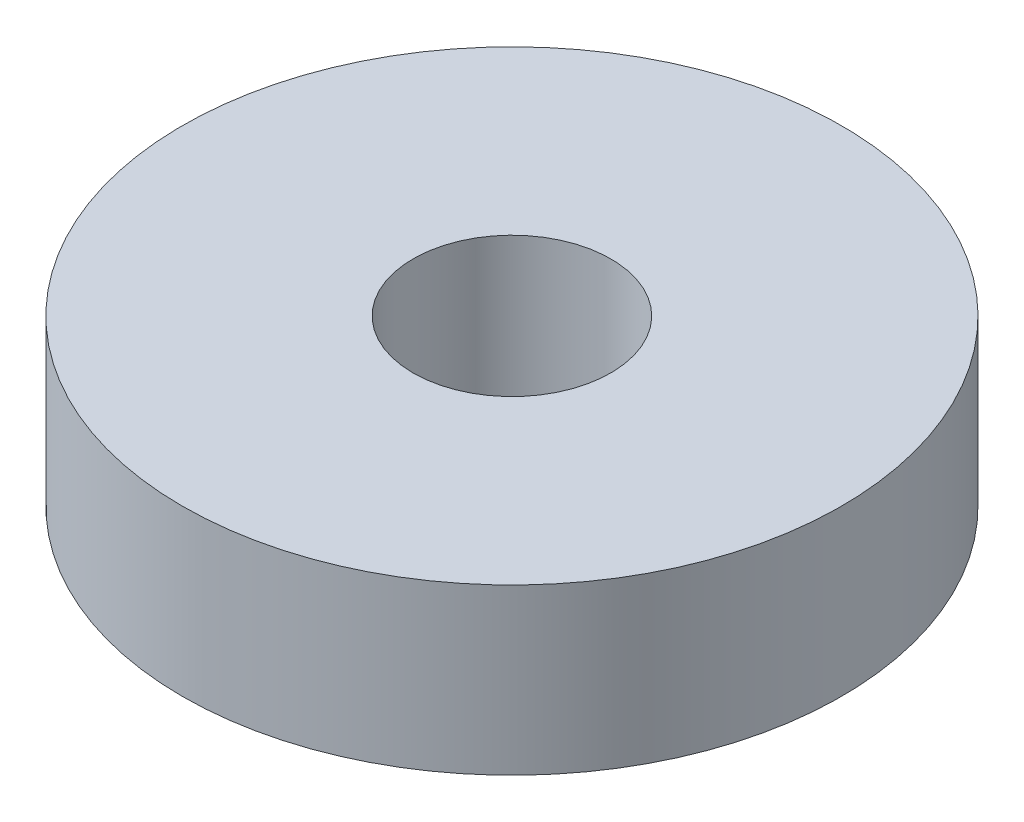
SolidWorks part; units mm, degrees
ref_plane "前视基准面" through (0, 0, 0) normal (0, 0, 1) x (1, 0, 0)
ref_plane "上视基准面" through (0, 0, 0) normal (0, 1, 0) x (1, 0, 0)
ref_plane "右视基准面" through (0, 0, 0) normal (1, 0, 0) x (0, 0, -1)
sketch "草图1" plane through (0, 0, 0) normal (0, 1, 0) x (1, 0, 0)
  circle A0 centre (0, 0) radius 10
  dimension "D1" = 20
extrude "凸台-拉伸1" add sketch "草图1" along normal blind 5
sketch "草图2" plane through (0, 5, 0) normal (0, 1, 0) x (1, 0, 0)
  circle A0 centre (0, 0) radius 3
  dimension "D1" = 6
extrude "切除-拉伸1" cut sketch "草图2" against normal through all
